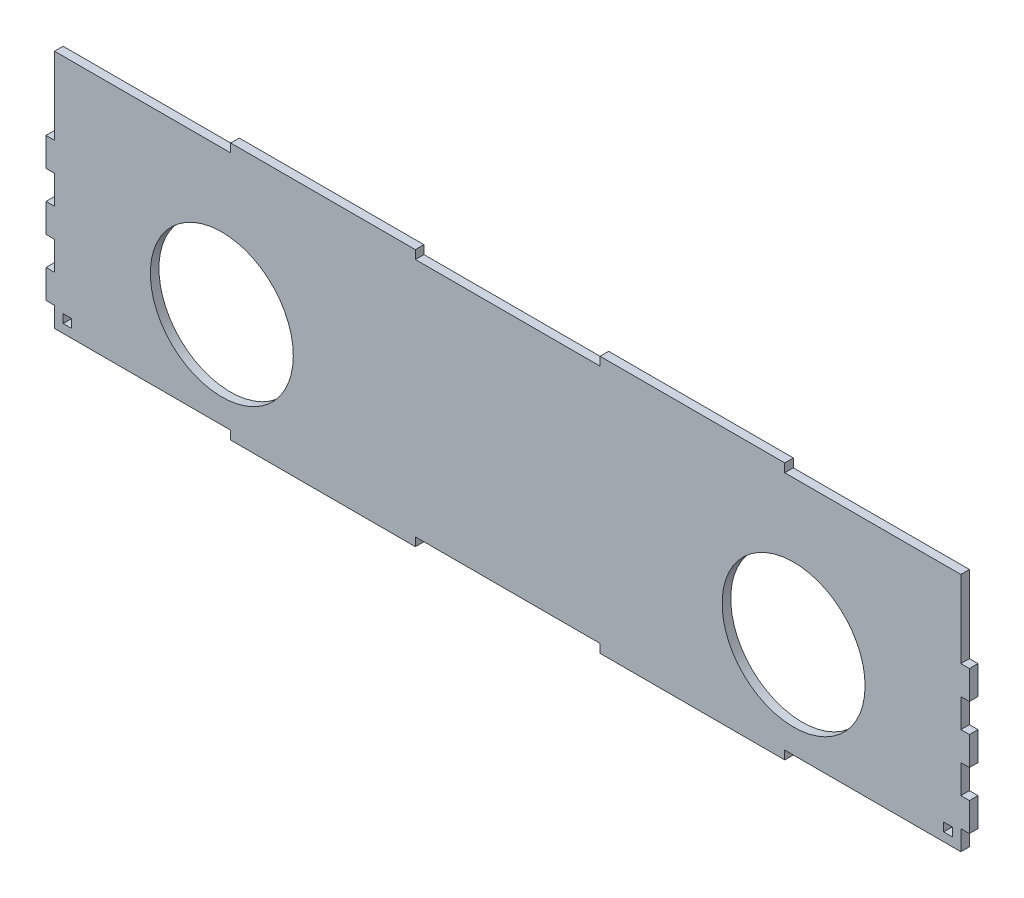
SolidWorks part; units mm, degrees
ref_plane "Front Plane" through (0, 0, 0) normal (0, 0, 1) x (1, 0, 0)
ref_plane "Top Plane" through (0, 0, 0) normal (0, 1, 0) x (1, 0, 0)
ref_plane "Right Plane" through (0, 0, 0) normal (1, 0, 0) x (0, 0, -1)
sketch "Sketch1" plane through (0, 0, 0) normal (0, 0, 1) x (1, 0, 0)
  line L0 (3, 87) -> (3, 60)
  line L1 (64.6, 90) -> (129.2, 90)
  line L2 (0, 50) -> (3, 50)
  line L3 (3, 3) -> (64.6, 3)
  line L4 (320, 87) -> (320, 60)
  line L5 (3, 60) -> (0, 60)
  line L6 (0, 60) -> (0, 50)
  line L7 (3, 50) -> (3, 40)
  line L8 (3, 40) -> (0, 40)
  line L9 (0, 40) -> (0, 30)
  line L10 (0, 30) -> (3, 30)
  line L11 (3, 30) -> (3, 20)
  line L12 (3, 20) -> (0, 20)
  line L13 (0, 20) -> (0, 10)
  line L14 (0, 10) -> (3, 10)
  line L15 (3, 10) -> (3, 3)
  line L16 (320, 60) -> (323, 60)
  line L17 (323, 60) -> (323, 50)
  line L18 (323, 50) -> (320, 50)
  line L19 (320, 50) -> (320, 40)
  line L20 (320, 40) -> (323, 40)
  line L21 (323, 40) -> (323, 30)
  line L22 (323, 30) -> (320, 30)
  line L23 (320, 30) -> (320, 20)
  line L24 (320, 20) -> (323, 20)
  line L25 (323, 20) -> (323, 10)
  line L26 (323, 10) -> (320, 10)
  line L27 (320, 10) -> (320, 3)
  line L28 (3, 87) -> (64.6, 87)
  line L29 (64.6, 87) -> (64.6, 90)
  line L30 (129.2, 90) -> (129.2, 87)
  line L31 (129.2, 87) -> (193.8, 87)
  line L32 (193.8, 87) -> (193.8, 90)
  line L33 (193.8, 90) -> (258.4, 90)
  line L34 (258.4, 90) -> (258.4, 87)
  line L35 (258.4, 87) -> (320, 87)
  line L36 (64.6, 3) -> (64.6, 0)
  line L37 (64.6, 0) -> (129.2, 0)
  line L38 (129.2, 0) -> (129.2, 3)
  line L39 (129.2, 3) -> (193.8, 3)
  line L40 (193.8, 3) -> (193.8, 0)
  line L41 (193.8, 0) -> (258.4, 0)
  line L42 (258.4, 0) -> (258.4, 3)
  line L43 (258.4, 3) -> (320, 3)
  line L44 (314, 6) -> (314, 9)
  line L45 (6, 6) -> (9, 6)
  line L46 (6, 6) -> (6, 9)
  line L47 (6, 9) -> (9, 9)
  line L48 (9, 6) -> (9, 9)
  line L49 (314, 9) -> (317, 9)
  line L50 (317, 6) -> (317, 9)
  line L51 (314, 6) -> (317, 6)
  circle A0 centre (61.5, 36.5) radius 25
  circle A1 centre (261.5, 36.5) radius 25
  dimension "D3" = 50
  dimension "D2" = 317
  dimension "D5" = 10
  dimension "D6" = 317
  dimension "D7" = 27
  dimension "D8" = 3
  dimension "D9" = 10
  dimension "D10" = 10
  dimension "D11" = 7
  dimension "D12" = 10
  dimension "D13" = 10
  dimension "D14" = 3
  dimension "D15" = 61.5
  dimension "D16" = 61.6
  dimension "D17" = 7
  dimension "D18" = 3
  dimension "D19" = 61.6
  dimension "D20" = 64.6
  dimension "D21" = 64.6
  dimension "D22" = 3
  dimension "D23" = 3
  dimension "D24" = 3
  dimension "D25" = 6
  dimension "D27" = 27
  dimension "D4" = 2
  dimension "D26" = 2
extrude "Boss-Extrude1" add sketch "Sketch1" along normal blind 3
